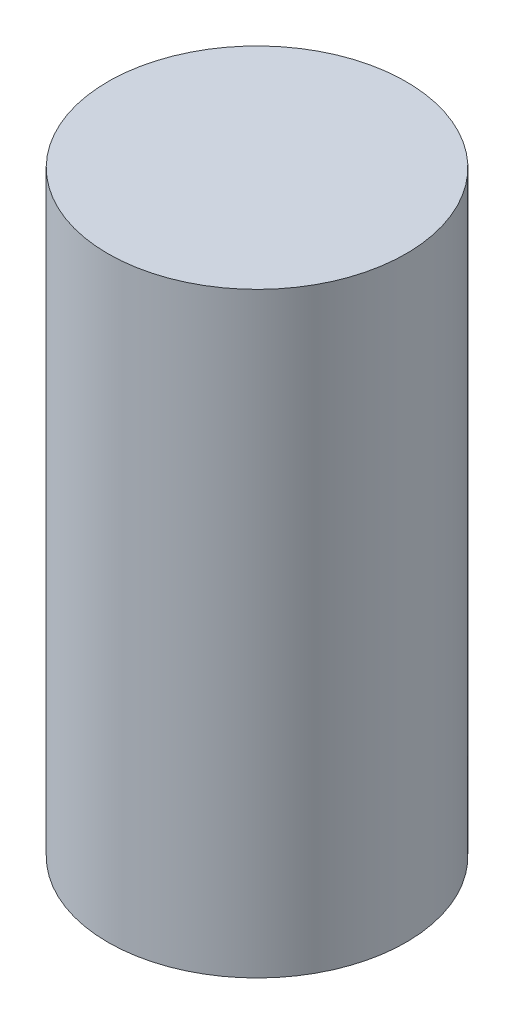
SolidWorks part; units mm, degrees
ref_plane "Front Plane" through (0, 0, 0) normal (0, 0, 1) x (1, 0, 0)
ref_plane "Top Plane" through (0, 0, 0) normal (0, 1, 0) x (1, 0, 0)
ref_plane "Right Plane" through (0, 0, 0) normal (1, 0, 0) x (0, 0, -1)
sketch "Sketch1" plane through (0, 0, 0) normal (0, 1, 0) x (1, 0, 0)
  circle A0 centre (0, 0) radius 1.5
  dimension "D1" = 3
extrude "Boss-Extrude1" add sketch "Sketch1" along normal blind 6 contours A0
